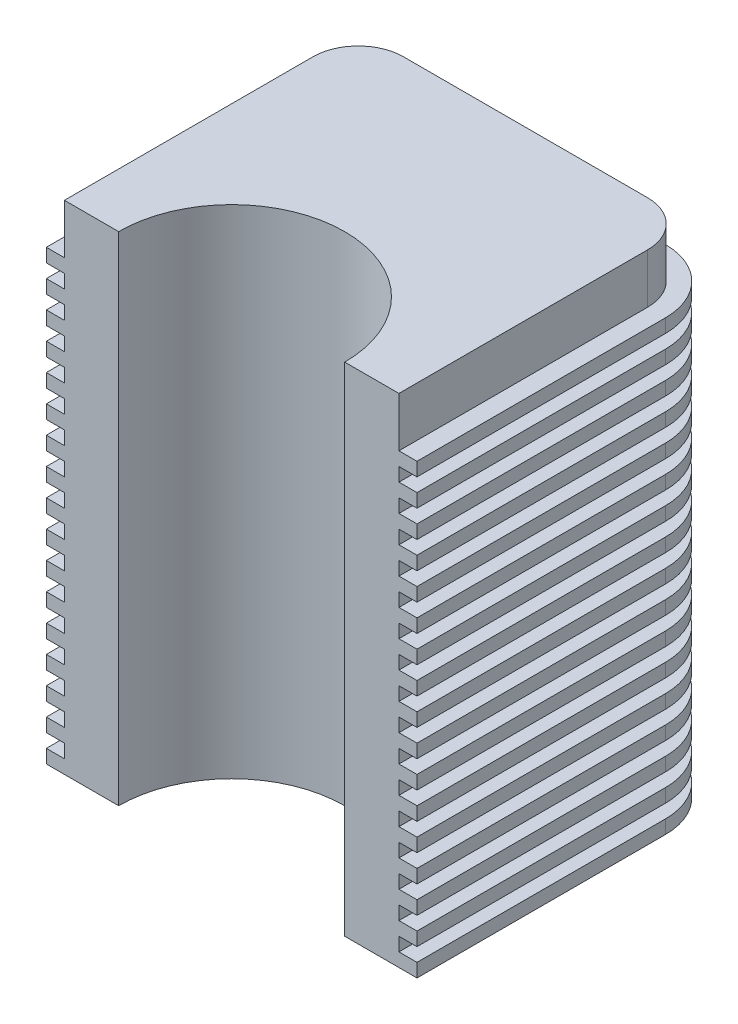
SolidWorks part; units mm, degrees
ref_plane "Front Plane" through (0, 0, 0) normal (0, 0, 1) x (1, 0, 0)
ref_plane "Top Plane" through (0, 0, 0) normal (0, 1, 0) x (1, 0, 0)
ref_plane "Right Plane" through (0, 0, 0) normal (1, 0, 0) x (0, 0, -1)
sketch "Sketch1" plane through (0, 0, 0) normal (0, 1, 0) x (1, 0, 0)
  line L0 (25, 0) -> (37, 0)
  line L1 (37, 0) -> (37, 55)
  line L2 (27, 65) -> (-27, 65)
  line L3 (0, 0) -> (0, 46.9913) construction
  line L4 (-25, 0) -> (-37, 0)
  line L5 (-37, 0) -> (-37, 55)
  arc A0 (25, 0) -> (-25, 0) centre (0, 0) ccw
  arc A1 (-27, 65) -> (-37, 55) centre (-27, 55) ccw
  arc A2 (27, 65) -> (37, 55) centre (27, 55) cw
  point P11 (0, 65)
  point P13 (-37, 65)
  point P16 (37, 65)
  dimension "D1" = 50
  dimension "D4" = 10
  dimension "D2" = 12
  dimension "D3" = 65
extrude "Boss-Extrude1" add sketch "Sketch1" along normal blind 110
sketch "Sketch3" plane through (0, 0, 0) normal (0, -1, 0) x (1, 0, 0)
  line L5 (-37, 0) -> (-41, 0)
  line L6 (37, 0) -> (41, 0)
  line L10 (-20.6155, 4) -> (-41, 4)
  line L11 (-41, 4) -> (-41, -55)
  line L12 (-27, -69) -> (27, -69)
  line L13 (41, -55) -> (41, 4)
  line L14 (41, 4) -> (20.6155, 4)
  line L16 (-41, 0) -> (-41, -55)
  line L17 (-27, -69) -> (27, -69)
  line L18 (41, -55) -> (41, 0)
  line L22 (-25, 0) -> (-37, 0)
  line L23 (-37, 0) -> (-37, -55)
  line L24 (-27, -65) -> (27, -65)
  line L25 (37, -55) -> (37, 0)
  line L26 (37, 0) -> (25, 0)
  line L28 (-37, 0) -> (-37, -55)
  line L29 (-27, -65) -> (27, -65)
  line L30 (37, -55) -> (37, 0)
  arc A6 (-20.6155, 4) -> (20.6155, 4) centre (0, 0) ccw
  arc A7 (-41, -55) -> (-27, -69) centre (-27, -55) ccw
  arc A8 (27, -69) -> (41, -55) centre (27, -55) ccw
  arc A10 (-41, -55) -> (-27, -69) centre (-27, -55) ccw
  arc A11 (27, -69) -> (41, -55) centre (27, -55) ccw
  arc A12 (-25, 0) -> (25, 0) centre (0, 0) ccw
  arc A13 (-37, -55) -> (-27, -65) centre (-27, -55) ccw
  arc A14 (27, -65) -> (37, -55) centre (27, -55) ccw
  arc A16 (-37, -55) -> (-27, -65) centre (-27, -55) ccw
  arc A17 (27, -65) -> (37, -55) centre (27, -55) ccw
  dimension "D1" = 4
  dimension "D2" = 0
extrude "Boss-Extrude2" add sketch "Sketch3" against normal blind 3
pattern_linear "LPattern1" count 17 spacing 6 along (0, 1, 0) of "Boss-Extrude2"
